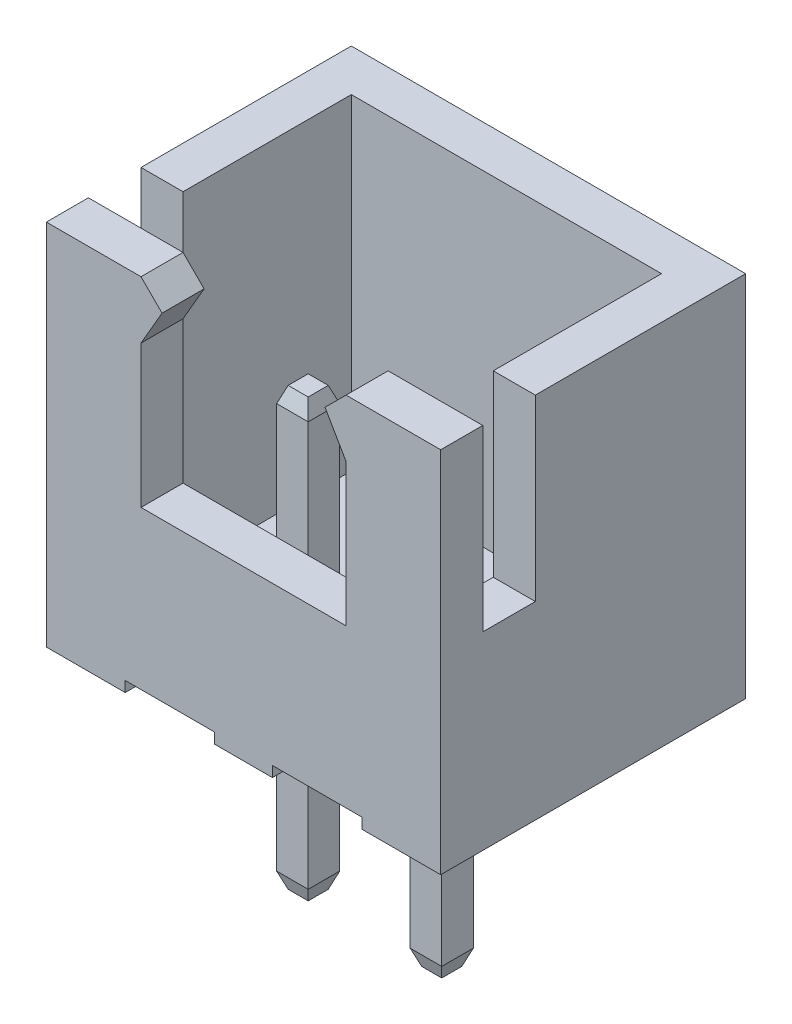
SolidWorks part; units mm, degrees
ref_plane "前视基准面" through (0, 0, 0) normal (0, 0, 1) x (1, 0, 0)
ref_plane "上视基准面" through (0, 0, 0) normal (0, 1, 0) x (1, 0, 0)
ref_plane "右视基准面" through (0, 0, 0) normal (1, 0, 0) x (0, 0, -1)
sketch "草图1" plane through (0, 0, 0) normal (0, 1, 0) x (1, 0, 0)
  line L1 (-3.75, -2.9) -> (3.75, -2.9)
  line L2 (-3.75, -2.9) -> (-3.75, 2.9)
  line L3 (-3.75, 2.9) -> (3.75, 2.9)
  line L4 (3.75, -2.9) -> (3.75, 2.9)
  line L5 (-3.75, -2.9) -> (3.75, 2.9) construction
  line L6 (-3.75, 2.9) -> (3.75, -2.9) construction
  point P0 (0, 0)
  dimension "D1" = 5.8
  dimension "D2" = 7.5
extrude "凸台-拉伸1" add sketch "草图1" along normal blind 7
sketch "草图2" plane through (0, 0, 0) normal (0, 0, 1) x (1, 0, 0)
  line L0 (-3.75, 0) -> (3.75, 0) construction
  line L1 (-2.25, 0) -> (-0.55, 0)
  line L2 (-2.25, 0) -> (-2.25, 0.2)
  line L3 (-2.25, 0.2) -> (-0.55, 0.2)
  line L4 (-0.55, 0) -> (-0.55, 0.2)
  line L5 (3.75, 7) -> (3.75, 0) construction
  line L6 (0.55, 0) -> (2.25, 0)
  line L7 (0.55, 0) -> (0.55, 0.2)
  line L8 (0.55, 0.2) -> (2.25, 0.2)
  line L9 (2.25, 0) -> (2.25, 0.2)
  line L10 (-3.75, 7) -> (-3.75, 0) construction
  line L11 (-3.75, 7) -> (3.75, 7) construction
  dimension "D1" = 1.5
  dimension "D2" = 1.5
  dimension "D3" = 1.7
  dimension "D4" = 0.2
  dimension "D5" = 6.8
extrude "切除-拉伸1" cut sketch "草图2" against normal through all both and the other way through all
sketch "草图3" plane through (0, 7, 0) normal (0, 1, 0) x (1, 0, 0)
  line L14 (-2.95, 2.1) -> (-2.95, -2.1)
  line L15 (-2.95, -2.1) -> (2.95, -2.1)
  line L16 (2.95, -2.1) -> (2.95, 2.1)
  line L17 (2.95, 2.1) -> (-2.95, 2.1)
  line L18 (-2.95, 2.1) -> (-2.95, -2.1)
  line L19 (-2.95, -2.1) -> (2.95, -2.1)
  line L20 (2.95, -2.1) -> (2.95, 2.1)
  line L21 (2.95, 2.1) -> (-2.95, 2.1)
  dimension "D1" = 0.8
extrude "切除-拉伸2" cut sketch "草图3" against normal blind 6.2
sketch "草图4" plane through (0, 0, 2.9) normal (0, 0, 1) x (1, 0, 0)
  line L0 (-1.95, 7) -> (-1.55, 6.6)
  line L1 (-3.75, 7) -> (3.75, 7) construction
  line L2 (-1.55, 6.6) -> (-1.95, 5.9072)
  line L3 (-1.95, 5.9072) -> (-1.95, 3.2)
  line L4 (-1.95, 3.2) -> (1.95, 3.2)
  line L5 (0, 0) -> (0, 8.3025) construction
  line L6 (-3.75, 7) -> (-3.75, 0) construction
  line L7 (-1.95, 7) -> (1.95, 7)
  line L8 (1.95, 5.9072) -> (1.95, 3.2)
  line L9 (1.55, 6.6) -> (1.95, 5.9072)
  line L10 (1.95, 7) -> (1.55, 6.6)
  point P13 (0, 3.2)
  point P14 (0, 7)
  dimension "D1" = 45
  dimension "D2" = 150
  dimension "D3" = 3.8
  dimension "D4" = 2.2
  dimension "D5" = 1.8
extrude "切除-拉伸3" cut sketch "草图4" against normal blind 1
sketch "草图5" plane through (0, 0, 0) normal (-1, 0, 0) x (0, 0, 1)
  line L0 (-2.9, 7) -> (2.9, 7) construction
  line L1 (1.1, 7) -> (2.1, 7)
  line L2 (1.1, 7) -> (1.1, 3.6)
  line L3 (1.1, 3.6) -> (2.1, 3.6)
  line L4 (2.1, 7) -> (2.1, 3.6)
  line L5 (2.9, 7) -> (2.9, 0) construction
  dimension "D1" = 3.4
  dimension "D2" = 0.8
  dimension "D3" = 1
extrude "切除-拉伸4" cut sketch "草图5" against normal through all both and the other way through all
sketch "草图6" plane through (0, 0.2, 0) normal (0, -1, 0) x (1, 0, 0)
  line L0 (0, 0) -> (0, 3.606) construction
  line L1 (-1.57, 0.7) -> (-0.97, 0.7)
  line L2 (-1.57, 0.7) -> (-1.57, 0.1)
  line L3 (-1.57, 0.1) -> (-0.97, 0.1)
  line L4 (-0.97, 0.7) -> (-0.97, 0.1)
  line L5 (-1.57, 0.7) -> (-0.97, 0.1) construction
  line L6 (-1.57, 0.1) -> (-0.97, 0.7) construction
  line L7 (-3.75, 2.9) -> (-2.25, 2.9) construction
  line L8 (1.57, 0.1) -> (0.97, 0.7) construction
  line L9 (1.57, 0.7) -> (0.97, 0.1) construction
  line L10 (0.97, 0.7) -> (0.97, 0.1)
  line L11 (1.57, 0.1) -> (0.97, 0.1)
  line L12 (1.57, 0.7) -> (1.57, 0.1)
  line L13 (1.57, 0.7) -> (0.97, 0.7)
  point P4 (-1.27, 0.4)
  point P5 (-1.1367, 0.9194)
  point P15 (1.27, 0.4)
  dimension "D1" = 0.6
  dimension "D2" = 2.54
  dimension "D3" = 2.5
extrude "凸台-拉伸3" add sketch "草图6" along normal offset from surface (4.2 mm away) 4 up to face at (-3, 0, 0) offset beyond the face yes
sketch "草图7" plane through (0, 0.8, 0) normal (0, 1, 0) x (1, 0, 0)
  line L4 (0.97, -0.1) -> (0.97, -0.7)
  line L5 (1.57, -0.1) -> (0.97, -0.1)
  line L6 (1.57, -0.7) -> (1.57, -0.1)
  line L7 (0.97, -0.7) -> (1.57, -0.7)
  line L8 (0.97, -0.1) -> (0.97, -0.7)
  line L9 (1.57, -0.1) -> (0.97, -0.1)
  line L10 (1.57, -0.7) -> (1.57, -0.1)
  line L11 (0.97, -0.7) -> (1.57, -0.7)
  line L12 (-1.57, -0.7) -> (-0.97, -0.7)
  line L13 (-0.97, -0.7) -> (-0.97, -0.1)
  line L14 (-0.97, -0.1) -> (-1.57, -0.1)
  line L15 (-1.57, -0.1) -> (-1.57, -0.7)
  line L16 (-1.57, -0.7) -> (-0.97, -0.7)
  line L17 (-0.97, -0.7) -> (-0.97, -0.1)
  line L18 (-0.97, -0.1) -> (-1.57, -0.1)
  line L19 (-1.57, -0.1) -> (-1.57, -0.7)
  dimension "D1" = 0
  dimension "D2" = 0
extrude "凸台-拉伸4" add sketch "草图7" along normal blind 3.5
chamfer "倒角1" distance 0.3 angle 20 16 edges at (0.97, 4.3, 0.4) (1.27, 4.3, 0.1) (1.57, 4.3, 0.4) (1.27, 4.3, 0.7) (-1.27, 4.3, 0.1) (-0.97, 4.3, 0.4) (-1.27, 4.3, 0.7) (-1.57, 4.3, 0.4) (0.97, -4, 0.4) (1.27, -4, 0.7) (1.57, -4, 0.4) (1.27, -4, 0.1) (-0.97, -4, 0.4) (-1.27, -4, 0.1) (-1.57, -4, 0.4) (-1.27, -4, 0.7)
